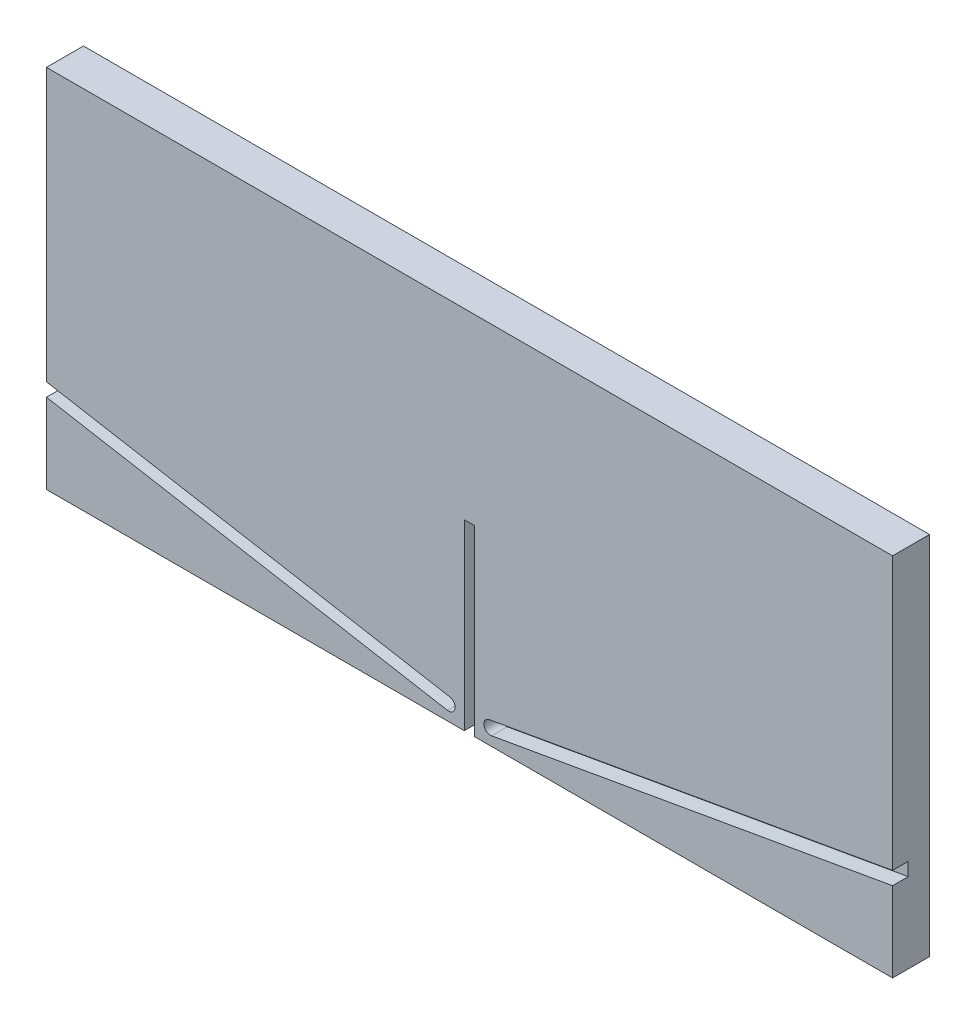
SolidWorks part; units mm, degrees
ref_plane "Front Plane" through (0, 0, 0) normal (0, 0, 1) x (1, 0, 0)
ref_plane "Top Plane" through (0, 0, 0) normal (0, 1, 0) x (1, 0, 0)
ref_plane "Right Plane" through (0, 0, 0) normal (1, 0, 0) x (0, 0, -1)
sketch "Sketch1" plane through (0, 0, 0) normal (0, 0, 1) x (1, 0, 0)
  line L1 (-102.87, -44.45) -> (102.87, -44.45)
  line L2 (-102.87, -44.45) -> (-102.87, 44.45)
  line L3 (-102.87, 44.45) -> (102.87, 44.45)
  line L4 (102.87, -44.45) -> (102.87, 44.45)
  line L5 (-102.87, -44.45) -> (102.87, 44.45) construction
  line L6 (-102.87, 44.45) -> (102.87, -44.45) construction
  point P0 (0, 0)
  dimension "D1" = 88.9
  dimension "D2" = 205.74
extrude "Boss-Extrude1" add sketch "Sketch1" along normal blind 8.9916
sketch "Sketch2" plane through (0, 0, 8.9916) normal (0, 0, 1) x (1, 0, 0)
  line L0 (-102.87, -44.45) -> (102.87, -44.45) construction
  line L1 (-1.27, 0) -> (1.27, 0)
  line L2 (-1.27, 0) -> (-1.27, -44.45)
  line L3 (-1.27, -44.45) -> (1.27, -44.45)
  line L4 (1.27, 0) -> (1.27, -44.45)
  line L5 (102.87, -44.45) -> (102.87, 44.45) construction
  line L6 (0, 0) -> (0, -31.75) construction
  dimension "D1" = 2.54
  dimension "D2" = 44.45
  dimension "D3" = 101.6
extrude "Cut-Extrude1" cut sketch "Sketch2" against normal blind 8.9916
sketch "Sketch4" plane through (0, 0, 8.9916) normal (0, 0, 1) x (1, 0, 0)
  line L0 (0, 0) -> (0, 44.45) construction
  line L2 (102.87, 44.45) -> (-102.87, 44.45) construction
  line L3 (-200.66, -6.154) -> (-5.08, -40.64) construction
  line L6 (-102.87, 44.45) -> (-102.87, -44.45) construction
  line L8 (-200.3843, -4.5906) -> (-4.8043, -39.0766)
  line L9 (-200.9357, -7.7174) -> (-5.3557, -42.2034)
  line L10 (-102.87, -44.45) -> (-1.27, -44.45) construction
  line L11 (-1.27, 0) -> (-1.27, -44.45) construction
  line L12 (200.66, -6.154) -> (5.08, -40.64) construction
  line L13 (200.3843, -4.5906) -> (4.8043, -39.0766)
  line L14 (200.9357, -7.7174) -> (5.3557, -42.2034)
  arc A0 (-200.3843, -4.5906) -> (-200.9357, -7.7174) centre (-200.66, -6.154) ccw
  arc A1 (-5.3557, -42.2034) -> (-4.8043, -39.0766) centre (-5.08, -40.64) ccw
  arc A2 (200.3843, -4.5906) -> (200.9357, -7.7174) centre (200.66, -6.154) cw
  arc A3 (5.3557, -42.2034) -> (4.8043, -39.0766) centre (5.08, -40.64) cw
  point P8 (-102.87, -23.397)
  point P20 (-4.445, -35.6264)
  point P21 (102.87, -23.397)
  dimension "D1" = 3.175
  dimension "D2" = 10
  dimension "D3" = 3.81
  dimension "D4" = 3.81
extrude "Cut-Extrude3" cut sketch "Sketch4" against normal blind 3.81
